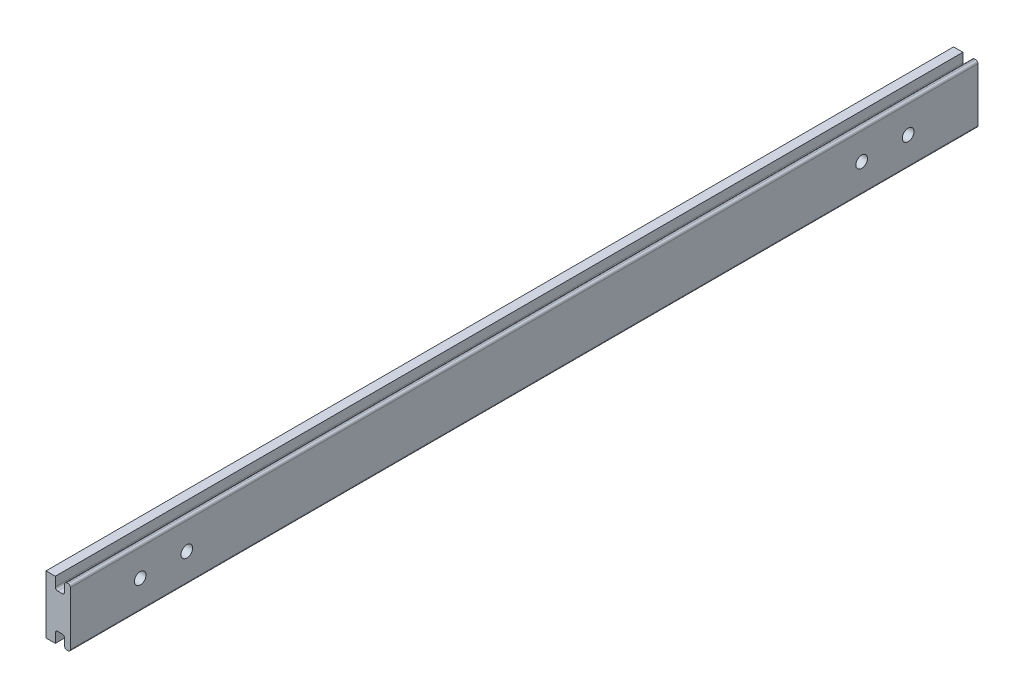
SolidWorks part; units mm, degrees
material "Brass"
ref_plane "Front Plane" through (0, 0, 0) normal (0, 0, 1) x (1, 0, 0)
ref_plane "Top Plane" through (0, 0, 0) normal (0, 1, 0) x (1, 0, 0)
ref_plane "Right Plane" through (0, 0, 0) normal (1, 0, 0) x (0, 0, -1)
sketch "Sketch3" plane through (0, 0, 0) normal (0, 0, 1) x (1, 0, 0)
  line L0 (-23.8235, 0) -> (35, 0) construction
  line L1 (-6, 12.5) -> (-6, -12.5)
  line L2 (-6, -12.5) -> (-2, -12.5)
  line L3 (-2, -12.5) -> (-2, -8.5)
  line L4 (-1, -7.5) -> (1, -7.5)
  line L5 (2, -8.5) -> (2, -12.5)
  line L6 (2, -12.5) -> (4.5, -12.5)
  line L7 (4.5, -12.5) -> (4.5, 12.5)
  line L8 (2, 12.5) -> (4.5, 12.5)
  line L9 (2, 8.5) -> (2, 12.5)
  line L10 (-1, 7.5) -> (1, 7.5)
  line L11 (-2, 12.5) -> (-2, 8.5)
  line L12 (-6, 12.5) -> (-2, 12.5)
  arc A0 (1, -7.5) -> (2, -8.5) centre (1, -8.5) cw
  arc A1 (-2, -8.5) -> (-1, -7.5) centre (-1, -8.5) cw
  arc A2 (2, 8.5) -> (1, 7.5) centre (1, 8.5) cw
  arc A3 (-1, 7.5) -> (-2, 8.5) centre (-1, 8.5) cw
  point P11 (0, -7.5)
  point P13 (4.5, 0)
  point P18 (-6, 0)
  point P20 (2, -7.5)
  point P23 (-2, -7.5)
  point P26 (2, 7.5)
  point P29 (-2, 7.5)
  dimension "D7" = 1
  dimension "D1" = 4
  dimension "D2" = 12.5
  dimension "D3" = 5
  dimension "D4" = 4
  dimension "D5" = 2.5
  dimension "D6" = 12.5
extrude "Boss-Extrude1" add sketch "Sketch3" along normal mid plane 390
sketch "Sketch4" plane through (-6, 0, 0) normal (-1, 0, 0) x (0, 0, 1)
  line L0 (-195, 0) -> (195, 0) construction
  line L1 (195, 12.5) -> (195, -12.5) construction
  line L2 (-195, 12.5) -> (-195, -12.5) construction
  line L3 (0, 0) -> (0, 12.5) construction
  line L4 (195, 12.5) -> (-195, 12.5) construction
  circle A0 centre (-165, 0) radius 2.5
  circle A1 centre (-145, 0) radius 2.5
  circle A2 centre (165, 0) radius 2.5
  circle A3 centre (145, 0) radius 2.5
  point P6 (0, 0)
  dimension "D1" = 5
  dimension "D3" = 5
  dimension "D2" = 30
  dimension "D4" = 20
extrude "Cut-Extrude1" cut sketch "Sketch4" against normal up to next
fillet "Fillet1" radius 1 4 edges at (2, -12.5, 0) (2, 12.5, 0) (4.5, 12.5, 0) (4.5, -12.5, 0)
